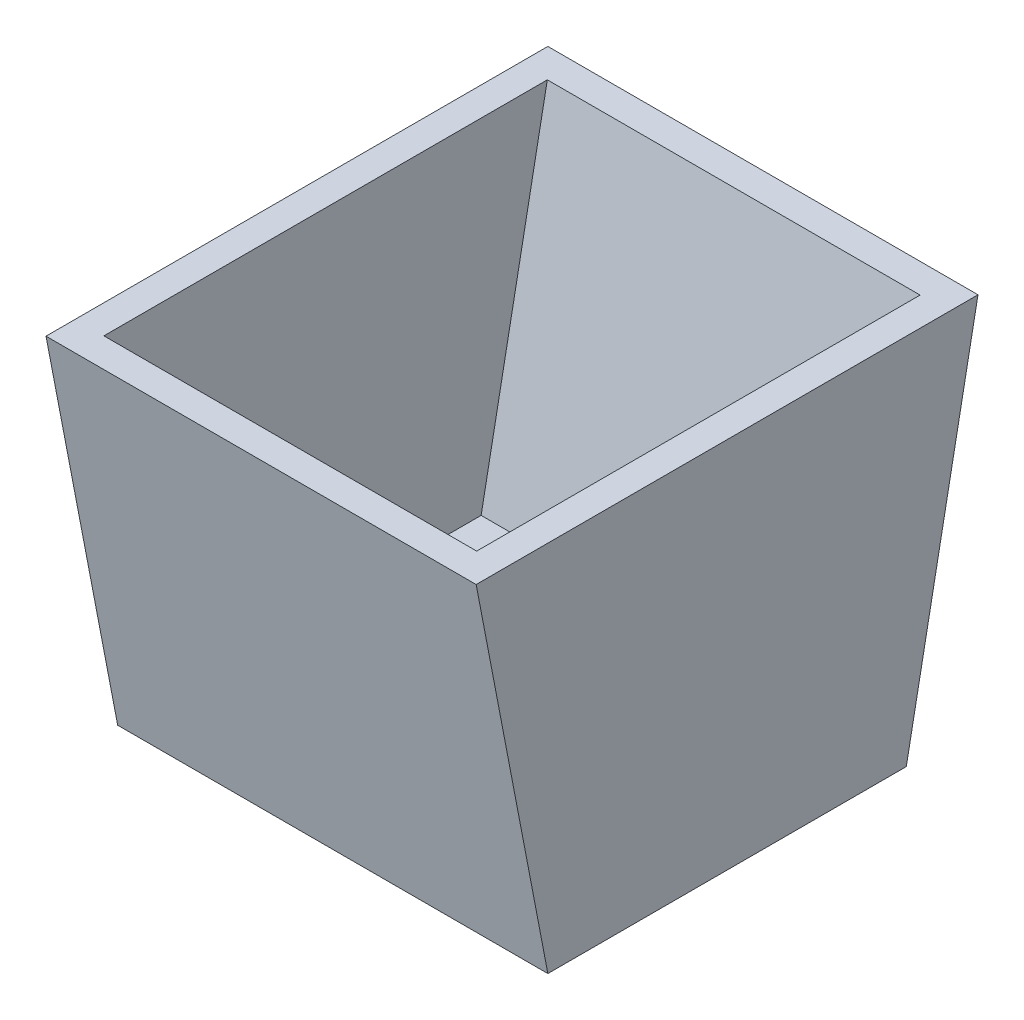
SolidWorks part; units mm, degrees
ref_plane "Front Plane" through (0, 0, 0) normal (0, 0, 1) x (1, 0, 0)
ref_plane "Top Plane" through (0, 0, 0) normal (0, 1, 0) x (1, 0, 0)
ref_plane "Right Plane" through (0, 0, 0) normal (1, 0, 0) x (0, 0, -1)
sketch "Sketch1" plane through (0, 0, 0) normal (1, 0, 0) x (0, 0, -1)
  line L0 (0, 0) -> (15, 0) construction
  line L1 (0, 0) -> (-15, 0) construction
  line L2 (0, 0) -> (0, -13) construction
  line L3 (0, 0) -> (0, 13) construction
  line L4 (17.5, 13) -> (-17.5, 13)
  line L5 (12.5, -13) -> (-12.5, -13)
  line L6 (-17.5, 13) -> (-12.5, -13)
  line L7 (17.5, 13) -> (12.5, -13)
  point P9 (0, 13)
  point P11 (0, -13)
  point P12 (0, 0)
  dimension "D1" = 15
  dimension "D2" = 25
  dimension "D3" = 35
  dimension "D4" = 13
extrude "Boss-Extrude1" add sketch "Sketch1" along normal blind 30
shell "Shell2" thickness 2
